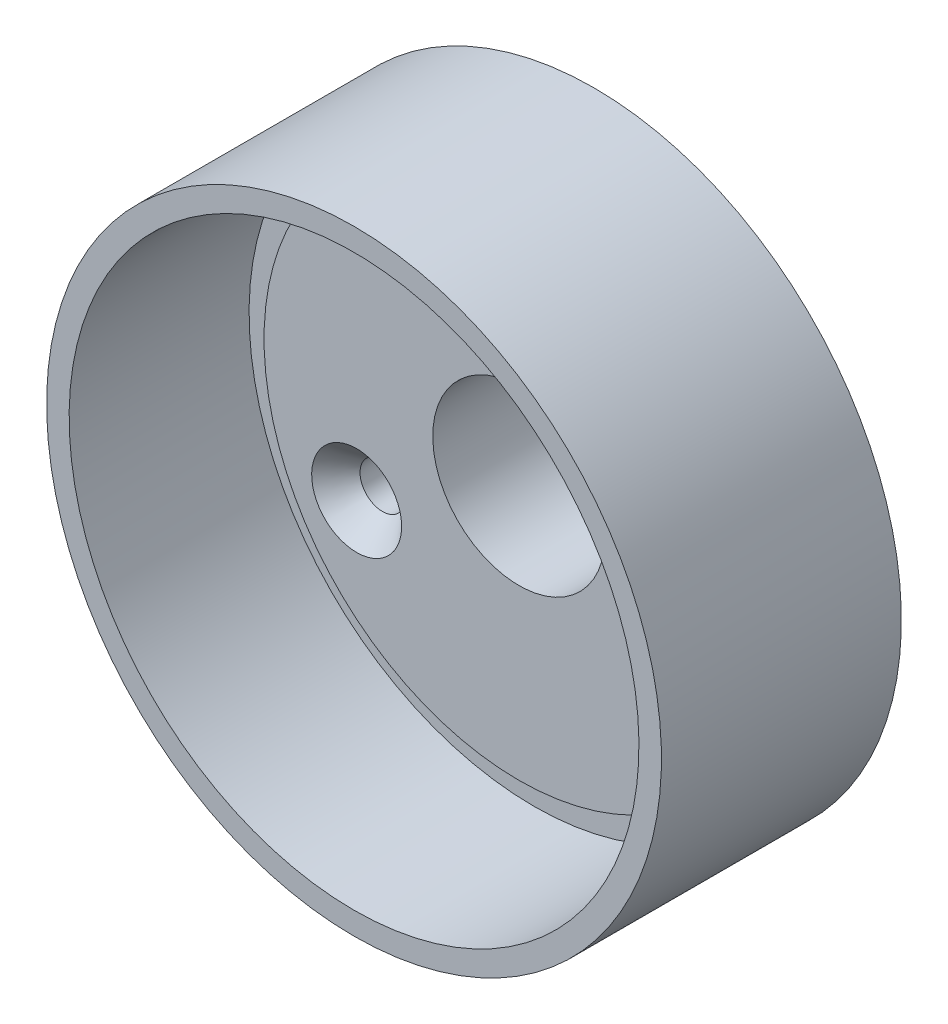
SolidWorks part; units mm, degrees
material "6063-T6"
ref_plane "Plan de face" through (0, 0, 0) normal (0, 0, 1) x (1, 0, 0)
ref_plane "Plan de dessus" through (0, 0, 0) normal (0, 1, 0) x (1, 0, 0)
ref_plane "Plan de droite" through (0, 0, 0) normal (1, 0, 0) x (0, 0, -1)
sketch "Esquisse2" plane through (0, 0, 0) normal (1, 0, 0) x (0, 0, -1)
  line L16 (0, 0) -> (0, 26.1937)
  line L17 (0, 26.1937) -> (-25.4, 26.1937)
  line L18 (-25.4, 26.1937) -> (-25.4, 65.0875)
  line L19 (-25.4, 65.0875) -> (-76.2, 65.0875)
  line L20 (-76.2, 65.0875) -> (-76.2, 60.325)
  line L21 (-76.2, 60.325) -> (-38.1, 60.325)
  line L22 (-38.1, 60.325) -> (-38.1, 53.975)
  line L23 (-38.1, 53.975) -> (-41.275, 53.975)
  line L24 (-41.275, 53.975) -> (-41.275, 0)
  line L28 (-41.275, 0) -> (0, 0)
  dimension "D1" = 50.8
  dimension "D2" = 76.2
  dimension "D3" = 34.925
  dimension "D4" = 6.35
  dimension "D5" = 3.175
  dimension "D6" = 60.325
  dimension "D7" = 65.0875
  dimension "D8" = 26.1937
revolve "Révolution2" add sketch "Esquisse2" angle 360 about L28
sketch "Esquisse3" plane through (0, 0, 0) normal (0, 0, -1) x (-1, 0, 0)
  circle A0 centre (0, 0) radius 18.2562
  dimension "D1" = 36.5125
extrude "Enlèv. mat.-Extru.1" cut sketch "Esquisse3" against normal through all
hole_wizard "Fraisage pour vis à tête fraisée bombée 3/81" positions "Esquisse4" profile "Esquisse5" countersink size "3/8" standard "Ansi Inch" end condition through all
sketch "Esquisse4" plane through (0, 0, 41.275) normal (0, 0, 1) x (1, 0, 0)
  point P0 (0, 39.6875)
  dimension "D1" = 39.6875
sketch "Esquisse5" plane through (0, 39.6875, 41.275) normal (1, 0, 0) x (0, -1, 0)
  line L0 (0, 0) -> (0, 41.275)
  line L1 (0, 41.275) -> (4.7625, 41.275)
  line L2 (4.7625, 41.275) -> (4.7625, 5.4786)
  line L3 (4.7625, 5.4786) -> (9.525, 0)
  line L5 (9.525, 0) -> (0, 0)
  line L6 (-4.7625, 5.4786) -> (-9.525, 0) construction
  line L11 (0, -6.35) -> (0, 107.95) construction
  dimension "Diamètre du perçage jusqu'au prochain" = 9.525
  dimension "Profondeur du perçage jusqu'au prochain" = 41.275
  dimension "Diamètre du fraisage entrant" = 19.05
  dimension "Angle du fraisage entrant" = 82
pattern_circular "Répétition circulaire1" count 3 over 360 about axis through (0, 0, 0) along (0, 0, 1) of "Fraisage pour vis à tête fraisée bombée 3/81"
chamfer "Chanfrein1" distance 1.5875 angle 45 1 edges at (0, -26.1937, 0)
hole_wizard "Trou taraudé 1/2-131" positions "Esquisse8" profile "Esquisse7" tap size "1/2-13" standard "Ansi Inch"
sketch "Esquisse8" plane through (0, 0, 0) normal (0, 1, 0) x (1, 0, 0)
  point P0 (0, -12.7)
  point P8 (0, -12.7)
  point P9 (0, 0)
  dimension "D1" = 12.7
sketch "Esquisse7" plane through (0, 0, 12.7) normal (1, 0, 0) x (0, 0, -1)
  line L0 (0, 0) -> (0, 65.0875)
  line L1 (0, 65.0875) -> (5.3581, 65.0875)
  line L2 (5.3581, 65.0875) -> (5.3581, 0)
  line L5 (5.3581, 0) -> (0, 0)
  line L11 (0, -6.35) -> (0, 107.95) construction
  dimension "Diamètre du trou pour taraudage jusqu'au prochain" = 10.7163
  dimension "Profondeur du trou pour taraudage jusqu'au prochain" = 65.0875
cosmetic thread "Filetage de perçage1" parameters "D2"=12.7
